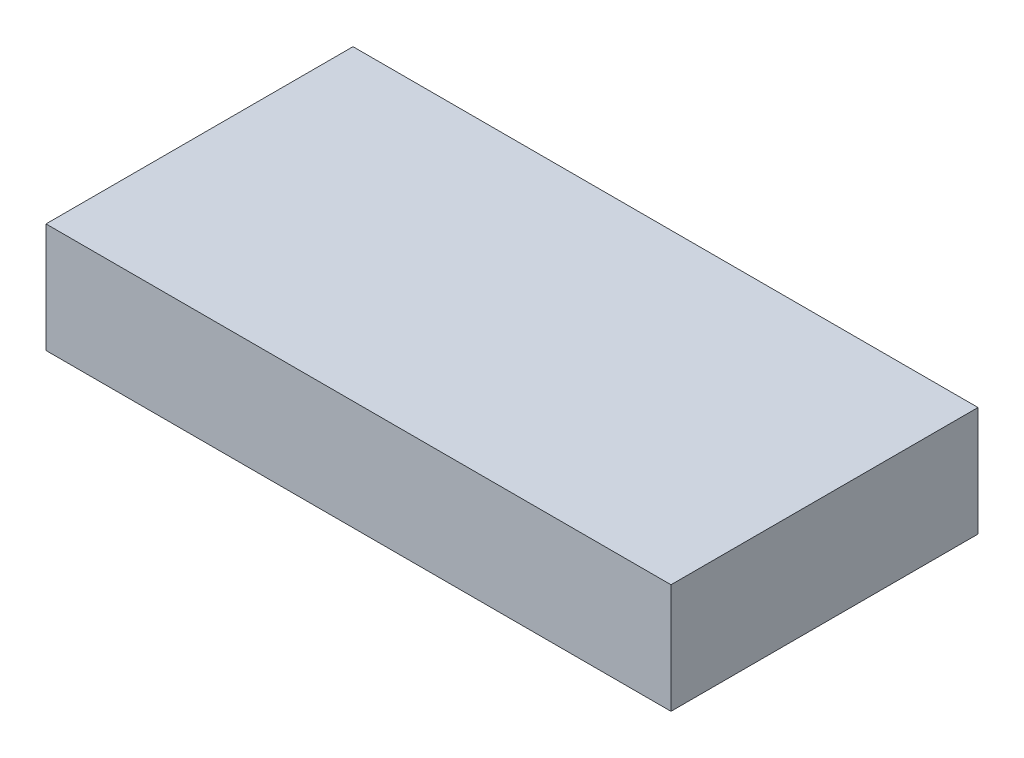
SolidWorks part; units mm, degrees
ref_plane "前视基准面" through (0, 0, 0) normal (0, 0, 1) x (1, 0, 0)
ref_plane "上视基准面" through (0, 0, 0) normal (0, 1, 0) x (1, 0, 0)
ref_plane "右视基准面" through (0, 0, 0) normal (1, 0, 0) x (0, 0, -1)
sketch "Sketch1" plane through (0, 0, 0) normal (0, 1, 0) x (1, 0, 0)
  line L1 (-28.5, 14) -> (28.5, 14)
  line L2 (-28.5, 14) -> (-28.5, -14)
  line L3 (-28.5, -14) -> (28.5, -14)
  line L4 (28.5, 14) -> (28.5, -14)
  line L5 (0, -14) -> (0, 14) construction
  line L6 (-28.5, 0) -> (28.5, 0) construction
  point P0 (0, 0)
  dimension "D1" = 57
  dimension "D2" = 28
extrude "Boss-Extrude1" add sketch "Sketch1" along normal blind 10
